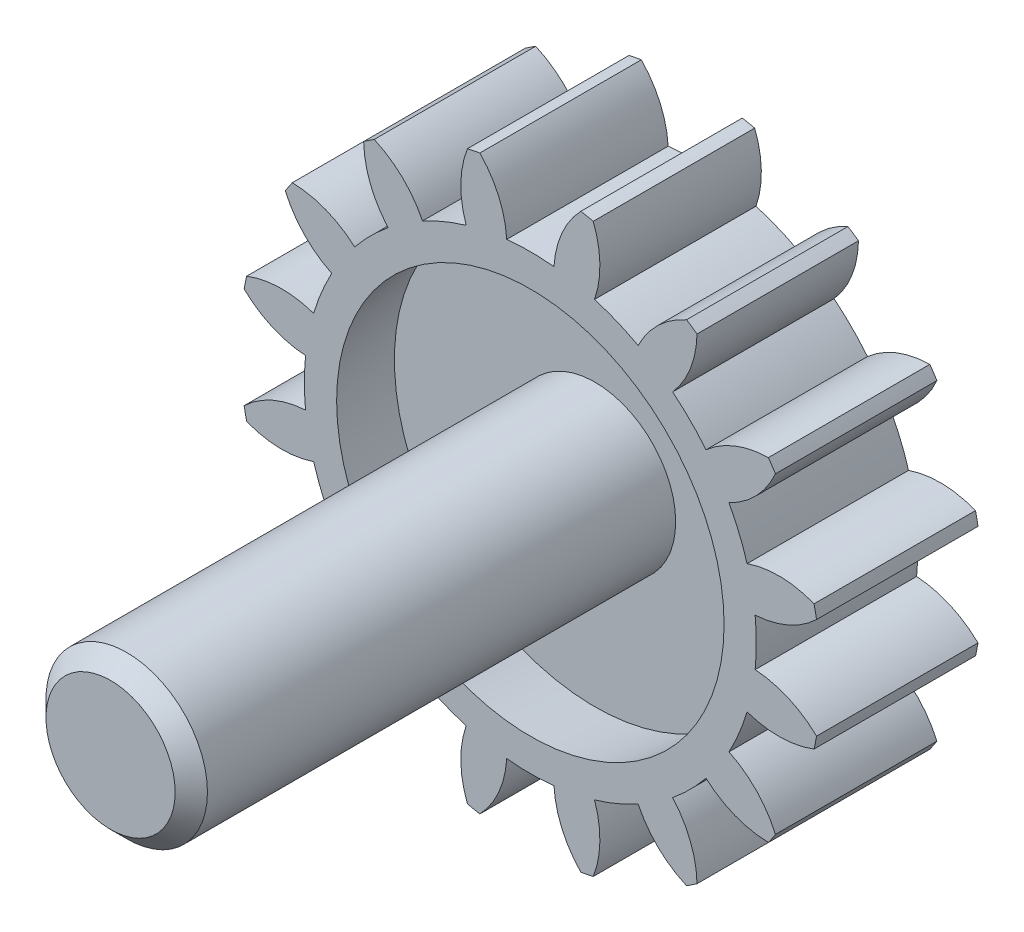
SolidWorks part; units mm, degrees
ref_plane "Спереди" through (0, 0, 0) normal (0, 0, 1) x (1, 0, 0)
ref_plane "Сверху" through (0, 0, 0) normal (0, 1, 0) x (1, 0, 0)
ref_plane "Справа" through (0, 0, 0) normal (1, 0, 0) x (0, 0, -1)
sketch "Эскиз1" plane through (0, 0, 0) normal (0, 0, 1) x (1, 0, 0)
  circle A0 centre (0, 0) radius 18
  dimension "D1" = 36
extrude "Бобышка-Вытянуть1" add sketch "Эскиз1" against normal blind 10
sketch "Эскиз3" plane through (0, 0, 0) normal (0, 0, 1) x (1, 0, 0)
  line L0 (0, 0) -> (0, 22.2182) construction
  line L1 (0, 0) -> (-2.3551, 22.4076) construction
  line L2 (0, 0) -> (-3.8678, 21.9355) construction
  arc A0 (1.4634, 13.9233) -> (-1.4634, 13.9233) centre (0, 0) ccw
  arc A1 (3.1257, 17.7265) -> (-3.1257, 17.7265) centre (0, 0) ccw
  circle A2 centre (0, 0) radius 18 construction
  arc A3 (-1.4634, 13.9233) -> (-3.1257, 17.7265) centre (-7.453, 13.5703) ccw
  arc A4 (1.4634, 13.9233) -> (3.1257, 17.7265) centre (7.453, 13.5703) cw
  arc A5 (6.6802, 12.3034) -> (3.9762, 13.4235) centre (0, 0) ccw
  arc A6 (3.9762, 13.4235) -> (3.8959, 17.5733) centre (-1.6925, 15.3895) ccw
  arc A7 (9.6714, 15.181) -> (3.8959, 17.5733) centre (0, 0) ccw
  arc A8 (6.6802, 12.3034) -> (9.6714, 15.181) centre (12.0788, 9.6852) cw
  arc A9 (10.88, 8.8105) -> (8.8105, 10.88) centre (0, 0) ccw
  arc A10 (8.8105, 10.88) -> (10.3244, 14.7447) centre (4.3256, 14.8657) ccw
  arc A11 (14.7447, 10.3244) -> (10.3244, 14.7447) centre (0, 0) ccw
  arc A12 (10.88, 8.8105) -> (14.7447, 10.3244) centre (14.8657, 4.3256) cw
  arc A13 (13.4235, 3.9762) -> (12.3034, 6.6802) centre (0, 0) ccw
  arc A14 (12.3034, 6.6802) -> (15.181, 9.6714) centre (9.6852, 12.0788) ccw
  arc A15 (17.5733, 3.8959) -> (15.181, 9.6714) centre (0, 0) ccw
  arc A16 (13.4235, 3.9762) -> (17.5733, 3.8959) centre (15.3895, -1.6925) cw
  arc A17 (13.9233, -1.4634) -> (13.9233, 1.4634) centre (0, 0) ccw
  arc A18 (13.9233, 1.4634) -> (17.7265, 3.1257) centre (13.5703, 7.453) ccw
  arc A19 (17.7265, -3.1257) -> (17.7265, 3.1257) centre (0, 0) ccw
  arc A20 (13.9233, -1.4634) -> (17.7265, -3.1257) centre (13.5703, -7.453) cw
  arc A21 (12.3034, -6.6802) -> (13.4235, -3.9762) centre (0, 0) ccw
  arc A22 (13.4235, -3.9762) -> (17.5733, -3.8959) centre (15.3895, 1.6925) ccw
  arc A23 (15.181, -9.6714) -> (17.5733, -3.8959) centre (0, 0) ccw
  arc A24 (12.3034, -6.6802) -> (15.181, -9.6714) centre (9.6852, -12.0788) cw
  arc A25 (8.8105, -10.88) -> (10.88, -8.8105) centre (0, 0) ccw
  arc A26 (10.88, -8.8105) -> (14.7447, -10.3244) centre (14.8657, -4.3256) ccw
  arc A27 (10.3244, -14.7447) -> (14.7447, -10.3244) centre (0, 0) ccw
  arc A28 (8.8105, -10.88) -> (10.3244, -14.7447) centre (4.3256, -14.8657) cw
  arc A29 (3.9762, -13.4235) -> (6.6802, -12.3034) centre (0, 0) ccw
  arc A30 (6.6802, -12.3034) -> (9.6714, -15.181) centre (12.0788, -9.6852) ccw
  arc A31 (3.8959, -17.5733) -> (9.6714, -15.181) centre (0, 0) ccw
  arc A32 (3.9762, -13.4235) -> (3.8959, -17.5733) centre (-1.6925, -15.3895) cw
  arc A33 (-1.4634, -13.9233) -> (1.4634, -13.9233) centre (0, 0) ccw
  arc A34 (1.4634, -13.9233) -> (3.1257, -17.7265) centre (7.453, -13.5703) ccw
  arc A35 (-3.1257, -17.7265) -> (3.1257, -17.7265) centre (0, 0) ccw
  arc A36 (-1.4634, -13.9233) -> (-3.1257, -17.7265) centre (-7.453, -13.5703) cw
  arc A37 (-6.6802, -12.3034) -> (-3.9762, -13.4235) centre (0, 0) ccw
  arc A38 (-3.9762, -13.4235) -> (-3.8959, -17.5733) centre (1.6925, -15.3895) ccw
  arc A39 (-9.6714, -15.181) -> (-3.8959, -17.5733) centre (0, 0) ccw
  arc A40 (-6.6802, -12.3034) -> (-9.6714, -15.181) centre (-12.0788, -9.6852) cw
  arc A41 (-10.88, -8.8105) -> (-8.8105, -10.88) centre (0, 0) ccw
  arc A42 (-8.8105, -10.88) -> (-10.3244, -14.7447) centre (-4.3256, -14.8657) ccw
  arc A43 (-14.7447, -10.3244) -> (-10.3244, -14.7447) centre (0, 0) ccw
  arc A44 (-10.88, -8.8105) -> (-14.7447, -10.3244) centre (-14.8657, -4.3256) cw
  arc A45 (-13.4235, -3.9762) -> (-12.3034, -6.6802) centre (0, 0) ccw
  arc A46 (-12.3034, -6.6802) -> (-15.181, -9.6714) centre (-9.6852, -12.0788) ccw
  arc A47 (-17.5733, -3.8959) -> (-15.181, -9.6714) centre (0, 0) ccw
  arc A48 (-13.4235, -3.9762) -> (-17.5733, -3.8959) centre (-15.3895, 1.6925) cw
  arc A49 (-13.9233, 1.4634) -> (-13.9233, -1.4634) centre (0, 0) ccw
  arc A50 (-13.9233, -1.4634) -> (-17.7265, -3.1257) centre (-13.5703, -7.453) ccw
  arc A51 (-17.7265, 3.1257) -> (-17.7265, -3.1257) centre (0, 0) ccw
  arc A52 (-13.9233, 1.4634) -> (-17.7265, 3.1257) centre (-13.5703, 7.453) cw
  arc A53 (-12.3034, 6.6802) -> (-13.4235, 3.9762) centre (0, 0) ccw
  arc A54 (-13.4235, 3.9762) -> (-17.5733, 3.8959) centre (-15.3895, -1.6925) ccw
  arc A55 (-15.181, 9.6714) -> (-17.5733, 3.8959) centre (0, 0) ccw
  arc A56 (-12.3034, 6.6802) -> (-15.181, 9.6714) centre (-9.6852, 12.0788) cw
  arc A57 (-8.8105, 10.88) -> (-10.88, 8.8105) centre (0, 0) ccw
  arc A58 (-10.88, 8.8105) -> (-14.7447, 10.3244) centre (-14.8657, 4.3256) ccw
  arc A59 (-10.3244, 14.7447) -> (-14.7447, 10.3244) centre (0, 0) ccw
  arc A60 (-8.8105, 10.88) -> (-10.3244, 14.7447) centre (-4.3256, 14.8657) cw
  arc A61 (-3.9762, 13.4235) -> (-6.6802, 12.3034) centre (0, 0) ccw
  arc A62 (-6.6802, 12.3034) -> (-9.6714, 15.181) centre (-12.0788, 9.6852) ccw
  arc A63 (-3.8959, 17.5733) -> (-9.6714, 15.181) centre (0, 0) ccw
  arc A64 (-3.9762, 13.4235) -> (-3.8959, 17.5733) centre (1.6925, 15.3895) cw
  dimension "D3" = 14
  dimension "D4" = 6
  dimension "D1" = 6
  dimension "D2" = 10
  dimension "D5" = 16
extrude "Вырез-Вытянуть2" cut sketch "Эскиз3" against normal through all
sketch "Эскиз4" plane through (0, 0, 0) normal (0, 0, 1) x (1, 0, 0)
  circle A0 centre (0, 0) radius 12
extrude "Вырез-Вытянуть3" cut sketch "Эскиз4" against normal blind 4 draft 6 draft outward yes
sketch "Эскиз5" plane through (0, 0, -4) normal (0, 0, 1) x (1, 0, 0)
  circle A0 centre (0, 0) radius 5
  circle A1 centre (0, 0) radius 12.4204 construction
  dimension "D1" = 10
extrude "Бобышка-Вытянуть2" add sketch "Эскиз5" along normal blind 30
chamfer "Фаска1" distance 1 angle 45 1 edges at (5, 0, 26)
sketch "Эскиз6" plane through (0, 0, -10) normal (0, 0, -1) x (-1, 0, 0)
  circle A0 centre (0, 0) radius 12
  dimension "D1" = 24
extrude "Вырез-Вытянуть4" cut sketch "Эскиз6" against normal blind 4 draft 6 draft outward yes
